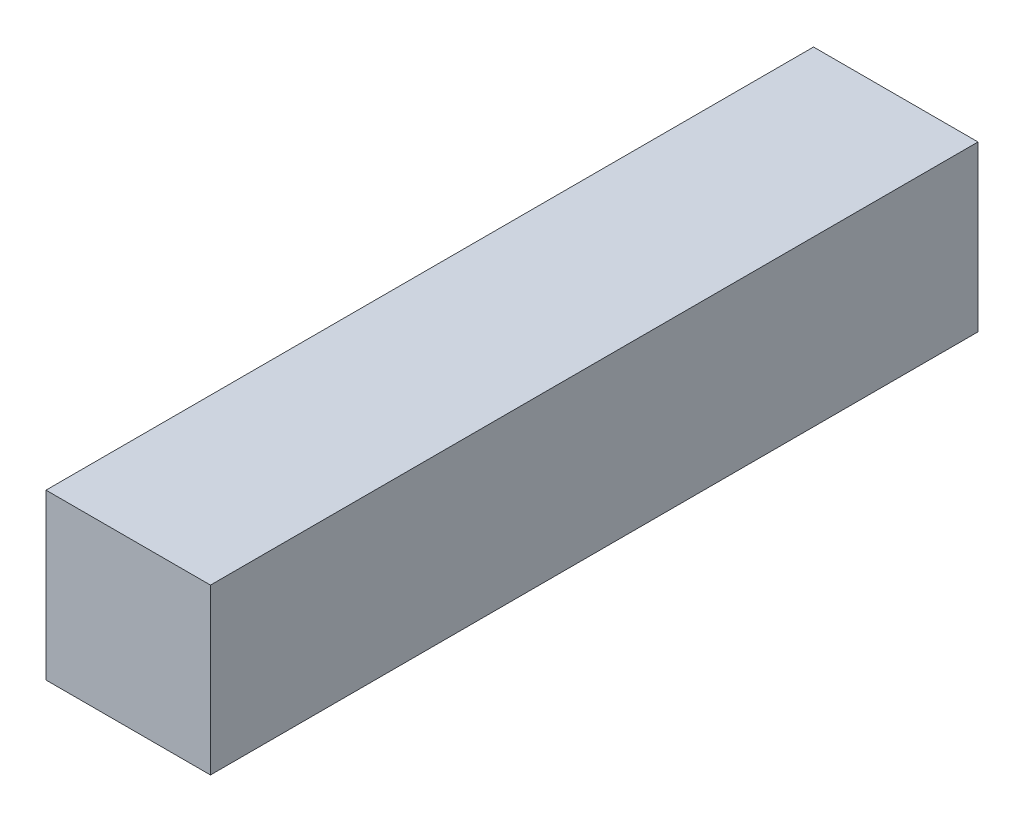
SolidWorks part; units mm, degrees
ref_plane "Front Plane" through (0, 0, 0) normal (0, 0, 1) x (1, 0, 0)
ref_plane "Top Plane" through (0, 0, 0) normal (0, 1, 0) x (1, 0, 0)
ref_plane "Right Plane" through (0, 0, 0) normal (1, 0, 0) x (0, 0, -1)
sketch "Sketch1" plane through (0, 0, 0) normal (0, 0, 1) x (1, 0, 0)
  line L1 (-1.5, -1.5) -> (1.5, -1.5)
  line L2 (-1.5, -1.5) -> (-1.5, 1.5)
  line L3 (-1.5, 1.5) -> (1.5, 1.5)
  line L4 (1.5, -1.5) -> (1.5, 1.5)
  line L5 (-1.5, -1.5) -> (1.5, 1.5) construction
  line L6 (-1.5, 1.5) -> (1.5, -1.5) construction
  point P0 (0, 0)
  dimension "D1" = 3
extrude "Boss-Extrude1" add sketch "Sketch1" along normal blind 14
